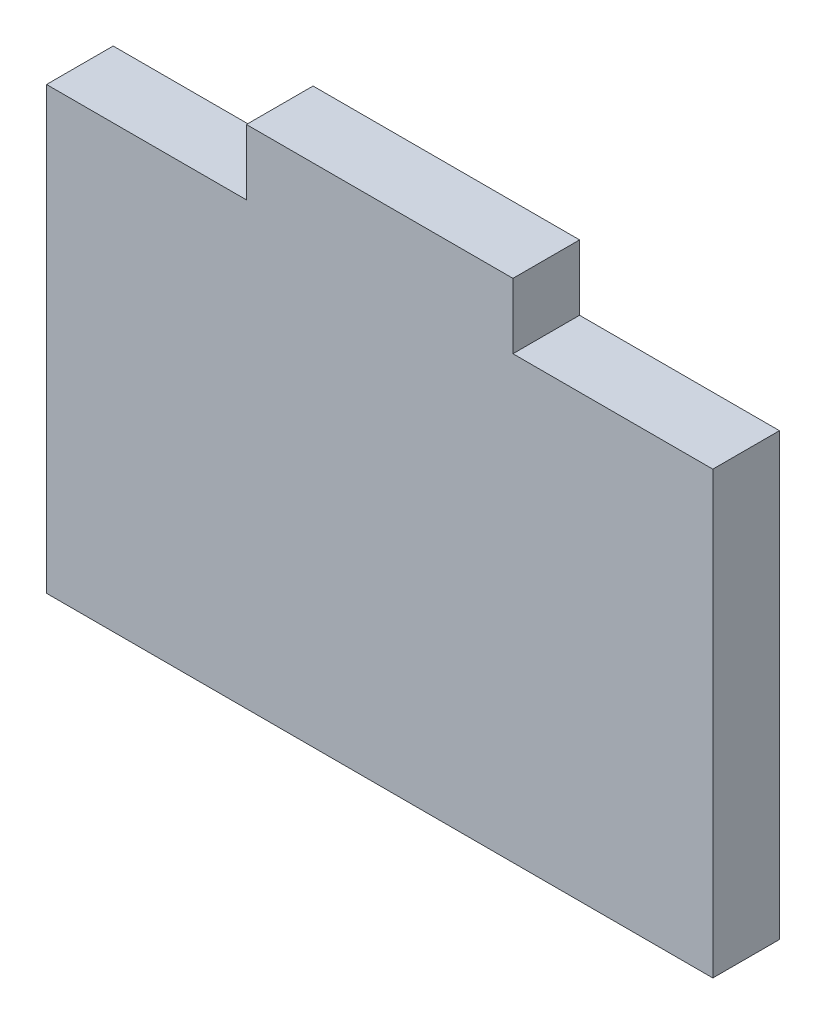
SolidWorks part; units mm, degrees
ref_plane "Front Plane" through (0, 0, 0) normal (0, 0, 1) x (1, 0, 0)
ref_plane "Top Plane" through (0, 0, 0) normal (0, 1, 0) x (1, 0, 0)
ref_plane "Right Plane" through (0, 0, 0) normal (1, 0, 0) x (0, 0, -1)
sketch "Sketch1" plane through (0, 0, 0) normal (0, 0, 1) x (1, 0, 0)
  line L0 (127, 50.8) -> (0, 50.8) construction
  line L1 (19.05, 0) -> (44.45, 0)
  line L2 (0, 0) -> (0, 101.6)
  line L3 (19.05, 101.6) -> (44.45, 101.6)
  line L6 (0, 0) -> (0, 6.223)
  line L7 (0, 6.223) -> (19.05, 6.223)
  line L8 (19.05, 0) -> (19.05, 6.223)
  line L10 (44.45, 0) -> (44.45, 6.223)
  line L11 (44.45, 6.223) -> (63.5, 6.223)
  line L21 (44.45, 95.377) -> (63.5, 95.377)
  line L24 (44.45, 101.6) -> (44.45, 95.377)
  line L25 (0, 95.377) -> (19.05, 95.377)
  line L26 (19.05, 101.6) -> (19.05, 95.377)
  line L28 (0, 101.6) -> (0, 95.377)
  line L29 (63.5, 95.377) -> (63.5, 6.223)
  dimension "D1" = 19.05
  dimension "D2" = 101.6
  dimension "D5" = 25.4
extrude "Boss-Extrude1" add sketch "Sketch1" along normal blind 6.35
sketch "Sketch2" plane through (0, 0, 6.35) normal (0, 0, 1) x (1, 0, 0)
  line L0 (0, 6.223) -> (0, 95.377) construction
  line L1 (0, 53.377) -> (63.8883, 53.377)
  line L2 (0, 53.377) -> (0, 0)
  line L3 (0, 0) -> (63.8883, 0)
  line L4 (63.8883, 53.377) -> (63.8883, 0)
  line L5 (0, 95.377) -> (19.05, 95.377) construction
  dimension "D1" = 42
extrude "Cut-Extrude1" cut sketch "Sketch2" against normal through all
